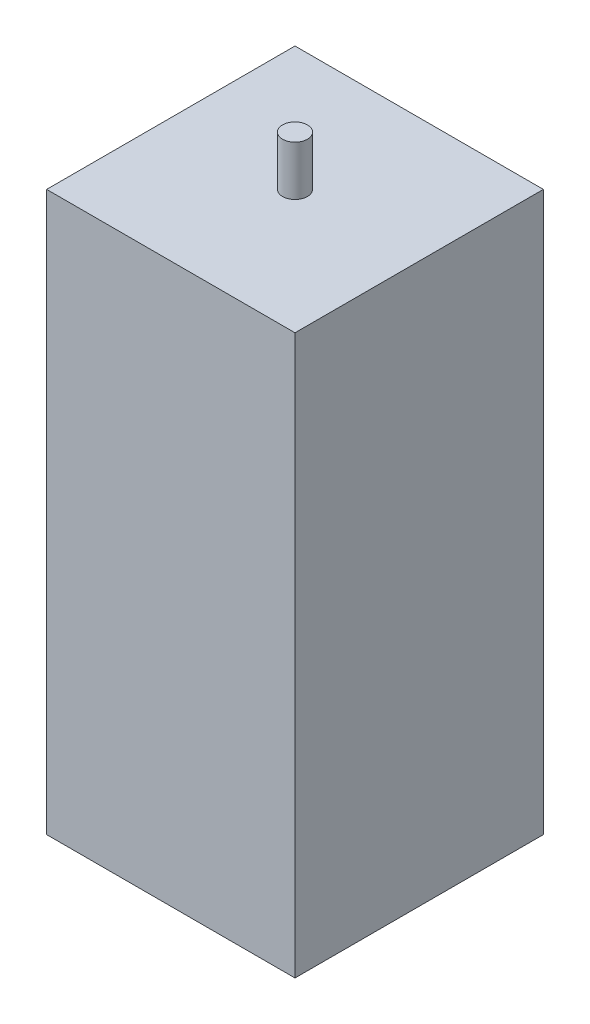
SolidWorks part; units mm, degrees
ref_plane "前视基准面" through (0, 0, 0) normal (0, 0, 1) x (1, 0, 0)
ref_plane "上视基准面" through (0, 0, 0) normal (0, 1, 0) x (1, 0, 0)
ref_plane "右视基准面" through (0, 0, 0) normal (1, 0, 0) x (0, 0, -1)
sketch "草图1" plane through (0, 0, 0) normal (0, 0, 1) x (1, 0, 0)
  line L0 (0, 69.3434) -> (0, -65.7797) construction
  line L1 (-5, 11.25) -> (5, 11.25)
  line L2 (-5, 11.25) -> (-5, -11.25)
  line L3 (-5, -11.25) -> (5, -11.25)
  line L4 (5, 11.25) -> (5, -11.25)
  line L5 (37.4584, 0) -> (-19.8575, 0) construction
  dimension "D1" = 22.5
  dimension "D2" = 10
extrude "凸台-拉伸1" add sketch "草图1" along normal blind 10
sketch "草图2" plane through (0, 11.25, 0) normal (0, 1, 0) x (1, 0, 0)
  line L0 (0, 2.6031) -> (0, -13.6541) construction
  line L1 (3.5518, -5) -> (-4.1173, -5) construction
  line L2 (5, 0) -> (-5, 0) construction
  line L3 (5, -10) -> (-5, -10) construction
  circle A0 centre (0, -5) radius 0.5
  dimension "D1" = 1
extrude "凸台-拉伸2" add sketch "草图2" along normal blind 2 and the other way blind 24.5
